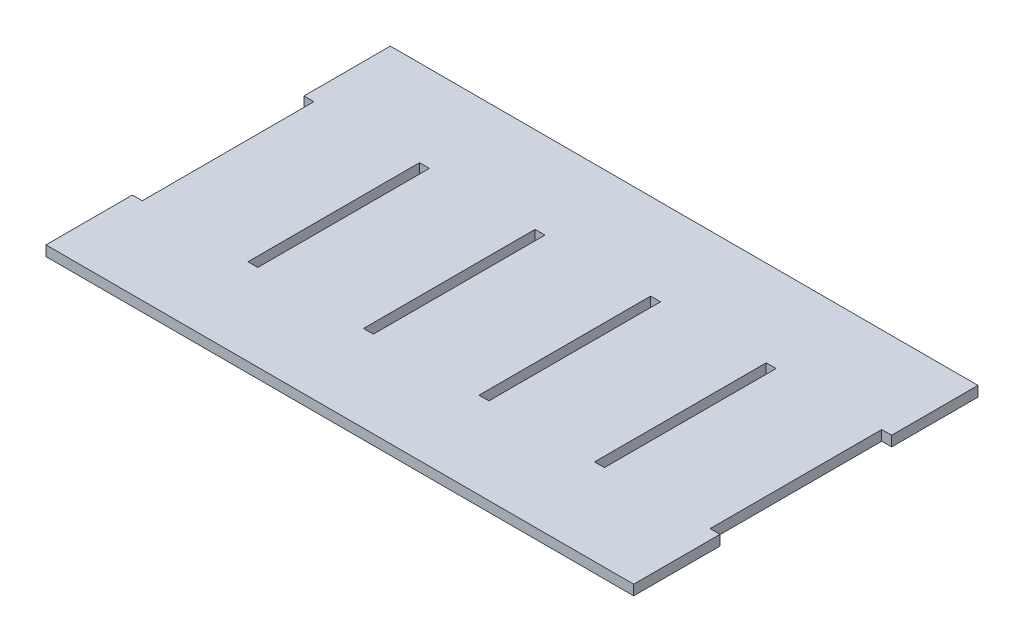
SolidWorks part; units mm, degrees
ref_plane "Front Plane" through (0, 0, 0) normal (0, 0, 1) x (1, 0, 0)
ref_plane "Top Plane" through (0, 0, 0) normal (0, 1, 0) x (1, 0, 0)
ref_plane "Right Plane" through (0, 0, 0) normal (1, 0, 0) x (0, 0, -1)
sketch "Sketch1" plane through (0, 0, 0) normal (0, 1, 0) x (1, 0, 0)
  line L1 (0, 0) -> (173.4, 0)
  line L2 (0, 0) -> (0, 101.6)
  line L3 (0, 101.6) -> (173.4, 101.6)
  line L4 (173.4, 0) -> (173.4, 101.6)
  dimension "D1" = 101.6
  dimension "D2" = 173.4
extrude "Boss-Extrude1" add sketch "Sketch1" along normal blind 3
sketch "Sketch2" plane through (0, 3, 0) normal (0, 1, 0) x (1, 0, 0)
  line L1 (2.92, 25.48) -> (0, 25.48)
  line L2 (2.92, 25.48) -> (2.92, 76.12)
  line L3 (2.92, 76.12) -> (0, 76.12)
  line L4 (0, 25.48) -> (0, 76.12)
  line L5 (0, 101.6) -> (0, 0) construction
  line L6 (0, 0) -> (173.4, 0) construction
  point P6 (0, 50.8)
  dimension "D1" = 2.92
  dimension "D2" = 50.64
  dimension "D3" = 0
  dimension "D4" = 50.8
extrude "Cut-Extrude1" cut sketch "Sketch2" against normal blind 3
pattern_linear "LPattern1" count 6 spacing 34.096 along (1, 0, 0) of "Cut-Extrude1"
equation "\"D2@Sketch1\"=6in+7*3mm"
